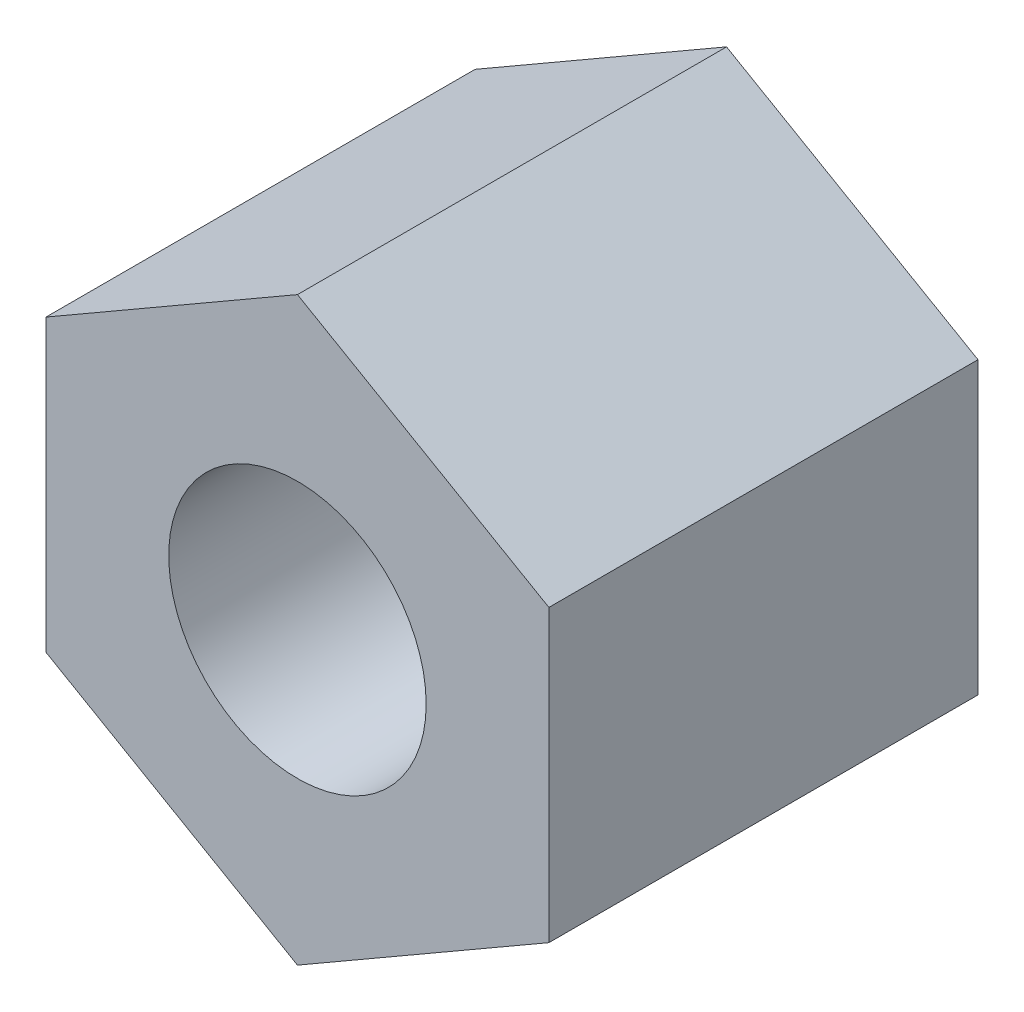
SolidWorks part; units mm, degrees
ref_plane "Plan de face" through (0, 0, 0) normal (0, 0, 1) x (1, 0, 0)
ref_plane "Plan de dessus" through (0, 0, 0) normal (0, 1, 0) x (1, 0, 0)
ref_plane "Plan de droite" through (0, 0, 0) normal (1, 0, 0) x (0, 0, -1)
sketch "Esquisse1" plane through (0, 0, 0) normal (0, 0, 1) x (1, 0, 0)
  line L1 (0, -3.3833) -> (2.93, -1.6916)
  line L2 (2.93, -1.6916) -> (2.93, 1.6916)
  line L3 (2.93, 1.6916) -> (0, 3.3833)
  line L4 (0, 3.3833) -> (-2.93, 1.6916)
  line L5 (-2.93, 1.6916) -> (-2.93, -1.6916)
  line L6 (-2.93, -1.6916) -> (0, -3.3833)
  circle A0 centre (0, 0) radius 1.5
  circle A1 centre (0, 0) radius 2.93 construction
  dimension "D1" = 3
  dimension "D2" = 5.86
extrude "Boss.-Extru.1" add sketch "Esquisse1" along normal blind 5
